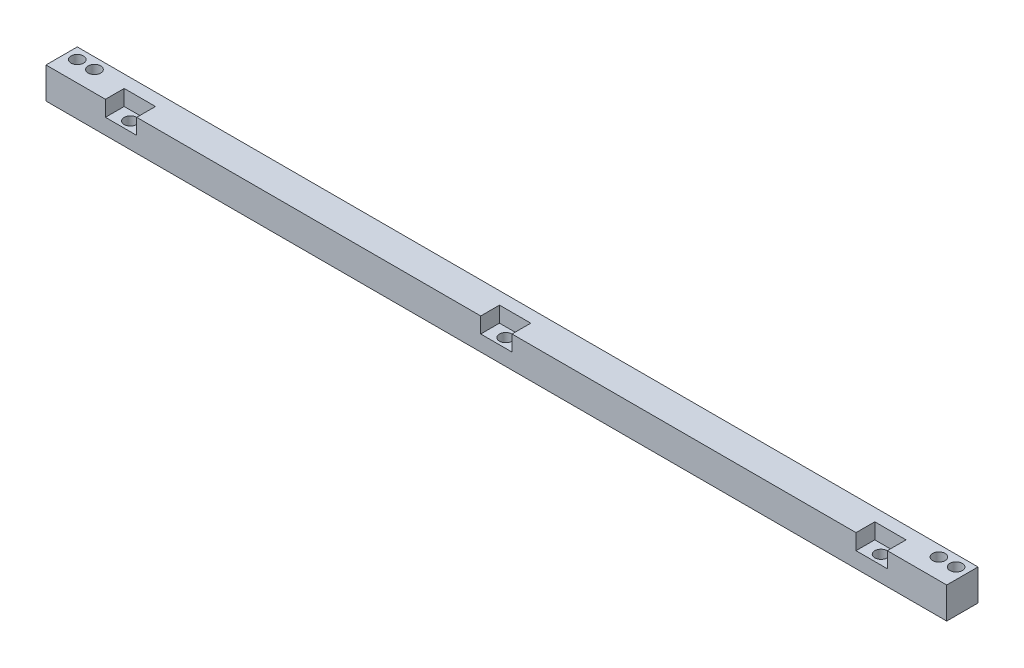
SolidWorks part; units mm, degrees
ref_plane "Front Plane" through (0, 0, 0) normal (0, 0, 1) x (1, 0, 0)
ref_plane "Top Plane" through (0, 0, 0) normal (0, 1, 0) x (1, 0, 0)
ref_plane "Right Plane" through (0, 0, 0) normal (1, 0, 0) x (0, 0, -1)
sketch "Sketch1" plane through (0, 0, 0) normal (0, 1, 0) x (1, 0, 0)
  line L1 (0, 0) -> (731.52, 0)
  line L2 (0, 0) -> (0, 25.4)
  line L3 (0, 25.4) -> (731.52, 25.4)
  line L4 (731.52, 0) -> (731.52, 25.4)
  dimension "D1" = 731.52
  dimension "D2" = 25.4
extrude "Boss-Extrude1" add sketch "Sketch1" along normal blind 25.4
sketch "Sketch2" plane through (0, 25.4, 0) normal (0, 1, 0) x (1, 0, 0)
  circle A0 centre (8.89, 16.51) radius 5.08
  circle A1 centre (22.86, 16.51) radius 5.08
  circle A2 centre (722.63, 16.51) radius 5.08
  circle A3 centre (708.66, 16.51) radius 5.08
  point P8 (0, 0)
  point P9 (0, 0)
  point P10 (0, 0)
extrude "Cut-Extrude1" cut sketch "Sketch2" against normal blind 27.94
sketch "Sketch3" plane through (0, 25.4, 0) normal (0, 1, 0) x (1, 0, 0)
  line L0 (0, 0) -> (731.52, 0) construction
  line L1 (48.26, 0) -> (73.66, 0)
  line L2 (48.26, 0) -> (48.26, 15.24)
  line L3 (48.26, 15.24) -> (73.66, 15.24)
  line L4 (73.66, 0) -> (73.66, 15.24)
  line L6 (683.26, 0) -> (657.86, 0)
  line L7 (683.26, 0) -> (683.26, 15.24)
  line L8 (683.26, 15.24) -> (657.86, 15.24)
  line L9 (657.86, 0) -> (657.86, 15.24)
  line L10 (353.06, 0) -> (378.46, 0)
  line L11 (353.06, 0) -> (353.06, 15.24)
  line L12 (353.06, 15.24) -> (378.46, 15.24)
  line L13 (378.46, 0) -> (378.46, 15.24)
  line L14 (353.06, 0) -> (378.46, 15.24) construction
  line L15 (353.06, 15.24) -> (378.46, 0) construction
  point P10 (365.76, 7.62)
extrude "Cut-Extrude2" cut sketch "Sketch3" against normal blind 12.7
sketch "Sketch4" plane through (0, 12.7, 0) normal (0, 1, 0) x (1, 0, 0)
  line L0 (353.06, 0) -> (378.46, 0) construction
  circle A0 centre (60.96, 7.62) radius 5.08
  circle A1 centre (670.56, 7.62) radius 5.08
  circle A2 centre (365.76, 7.62) radius 5.08
  point P8 (365.76, 0)
  point P9 (353.06, 7.62)
  dimension "D1" = 7.62
extrude "Cut-Extrude3" cut sketch "Sketch4" against normal blind 15.24
